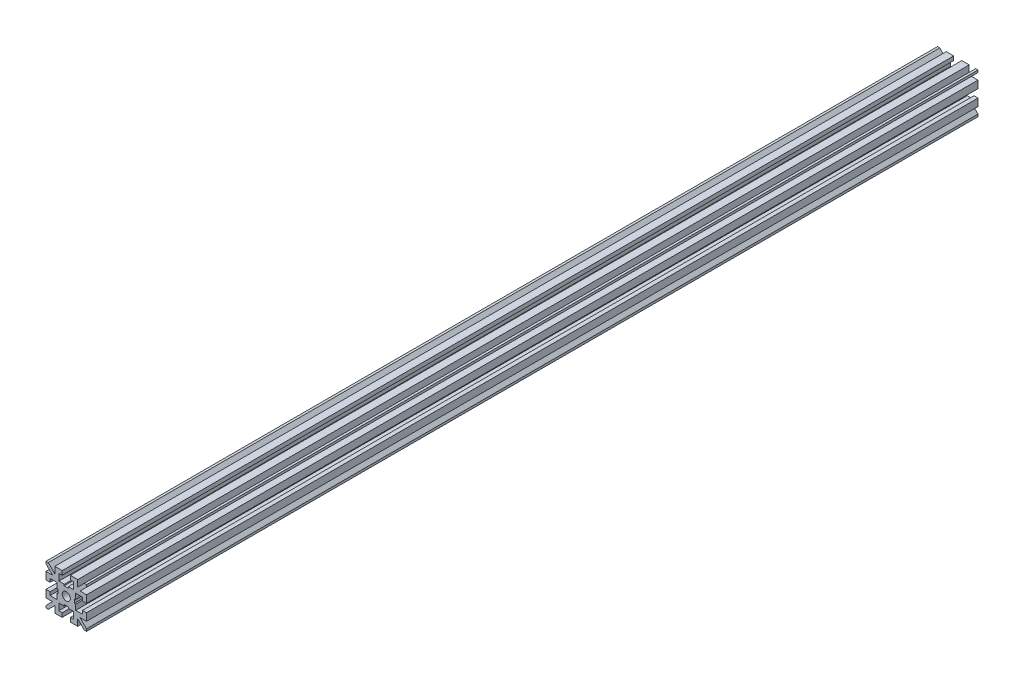
SolidWorks part; units mm, degrees
ref_plane "Front Plane" through (0, 0, 0) normal (0, 0, 1) x (1, 0, 0)
ref_plane "Top Plane" through (0, 0, 0) normal (0, 1, 0) x (1, 0, 0)
ref_plane "Right Plane" through (0, 0, 0) normal (1, 0, 0) x (0, 0, -1)
sketch "Sketch1" plane through (0, 0, 0) normal (0, 0, 1) x (1, 0, 0)
  line L1 (-9.0006, 3.7616) -> (5.9994, 3.7616)
  line L2 (-9.0006, 3.7616) -> (-9.0006, -11.2384)
  line L3 (-9.0006, -11.2384) -> (5.9994, -11.2384)
  line L4 (5.9994, 3.7616) -> (5.9994, -11.2384)
  dimension "D1" = 15
  dimension "D2" = 15
extrude "Boss-Extrude1" add sketch "Sketch1" along normal blind 330
sketch "Sketch2" plane through (0, 0, 330) normal (0, 0, 1) x (1, 0, 0)
  line L0 (-9.0006, 3.7616) -> (5.9994, -11.2384) construction
  line L1 (5.9994, 3.7616) -> (-9.0006, -11.2384) construction
  line L4 (1.9994, -4.4884) -> (1.9994, -6.4884)
  line L5 (5.9994, -3.7384) -> (1.9994, -3.7384) construction
  line L6 (5.9994, -11.2384) -> (5.9994, 3.7616) construction
  line L7 (-1.5006, 3.7616) -> (-1.5006, -3.7384) construction
  line L8 (5.9994, 3.7616) -> (-9.0006, 3.7616) construction
  line L9 (-9.0006, -3.7384) -> (-1.5006, -3.7384) construction
  line L10 (-9.0006, 3.7616) -> (-9.0006, -11.2384) construction
  line L11 (-1.5006, -11.2384) -> (-1.5006, -3.7384) construction
  line L12 (-9.0006, -11.2384) -> (5.9994, -11.2384) construction
  line L13 (1.9994, -4.4884) -> (1.4994, -4.4884)
  line L14 (1.9994, -0.9884) -> (4.4994, -0.9884)
  line L15 (1.9994, -0.9884) -> (1.9994, -2.9884)
  line L16 (1.9994, -6.4884) -> (4.4994, -6.4884)
  line L17 (4.4994, -0.9884) -> (4.4994, -6.4884)
  line L18 (-4.2506, -7.2384) -> (-4.2506, -9.7384)
  line L19 (1.9994, -2.9884) -> (1.4994, -2.9884)
  line L20 (1.4994, -4.4884) -> (1.4994, -2.9884)
  line L21 (1.4994, -3.7384) -> (-0.0006, -3.7384) construction
  line L22 (-2.2506, -7.2384) -> (-4.2506, -7.2384)
  line L23 (-2.2506, -7.2384) -> (-2.2506, -6.7384)
  line L24 (-2.2506, -6.7384) -> (-0.7506, -6.7384)
  line L25 (-0.7506, -7.2384) -> (-0.7506, -6.7384)
  line L26 (1.2494, -7.2384) -> (-0.7506, -7.2384)
  line L27 (1.2494, -7.2384) -> (1.2494, -9.7384)
  line L28 (1.2494, -9.7384) -> (-4.2506, -9.7384)
  line L29 (-5.0006, -0.9884) -> (-7.5006, -0.9884)
  line L30 (-5.0006, -2.9884) -> (-5.0006, -0.9884)
  line L31 (-5.0006, -2.9884) -> (-4.5006, -2.9884)
  line L32 (-4.5006, -2.9884) -> (-4.5006, -4.4884)
  line L33 (-5.0006, -4.4884) -> (-4.5006, -4.4884)
  line L34 (-5.0006, -6.4884) -> (-5.0006, -4.4884)
  line L35 (-5.0006, -6.4884) -> (-7.5006, -6.4884)
  line L36 (-7.5006, -6.4884) -> (-7.5006, -0.9884)
  line L37 (1.2494, -0.2384) -> (1.2494, 2.2616)
  line L38 (-0.7506, -0.2384) -> (1.2494, -0.2384)
  line L39 (-0.7506, -0.2384) -> (-0.7506, -0.7384)
  line L40 (-0.7506, -0.7384) -> (-2.2506, -0.7384)
  line L41 (-2.2506, -0.2384) -> (-2.2506, -0.7384)
  line L42 (-4.2506, -0.2384) -> (-2.2506, -0.2384)
  line L43 (-4.2506, -0.2384) -> (-4.2506, 2.2616)
  line L44 (-4.2506, 2.2616) -> (1.2494, 2.2616)
  circle A0 centre (-1.5006, -3.7384) radius 1.5
  point P60 (-1.5006, -3.7384)
  dimension "D1" = 5.5
  dimension "D2" = 2.5
  dimension "D3" = 1.5
  dimension "D4" = 2.75
  dimension "D5" = 0.5
  dimension "D6" = 1.5
  dimension "D7" = 0.75
  dimension "D8" = 4
extrude "Cut-Extrude1" cut sketch "Sketch2" against normal blind 330
sketch "Sketch3" plane through (0, 0, 330) normal (0, 0, 1) x (1, 0, 0)
  line L0 (5.9994, 3.7616) -> (-9.0006, -11.2384) construction
  line L1 (-9.0006, 3.7616) -> (5.9994, -11.2384) construction
  line L2 (5.1509, 3.7616) -> (2.7494, 1.3602)
  line L3 (5.9994, 3.7616) -> (-9.0006, 3.7616) construction
  line L4 (2.7494, 1.3602) -> (2.7494, 3.7616)
  line L5 (2.7494, 3.7616) -> (5.1509, 3.7616)
  line L6 (1.2494, -0.2384) -> (1.2494, 2.2616) construction
  line L7 (5.9994, 0.5116) -> (5.9994, 2.9131)
  line L8 (3.5979, 0.5116) -> (5.9994, 0.5116)
  line L9 (5.9994, 2.9131) -> (3.5979, 0.5116)
  line L10 (1.2494, 2.2616) -> (-4.2506, 2.2616) construction
  line L11 (-3.0006, 3.7616) -> (-0.0006, 3.7616)
  line L12 (-3.0006, 3.7616) -> (-3.0006, 2.2616)
  line L13 (-3.0006, 2.2616) -> (-0.0006, 2.2616)
  line L14 (-0.0006, 3.7616) -> (-0.0006, 2.2616)
  line L15 (-2.2506, -0.7384) -> (-0.7506, -0.7384) construction
  line L16 (2.7494, -8.8369) -> (2.7494, -11.2384)
  line L17 (2.7494, -11.2384) -> (5.1509, -11.2384)
  line L18 (5.1509, -11.2384) -> (2.7494, -8.8369)
  line L19 (5.9994, -10.3898) -> (3.5979, -7.9884)
  line L20 (3.5979, -7.9884) -> (5.9994, -7.9884)
  line L21 (5.9994, -7.9884) -> (5.9994, -10.3898)
  line L22 (5.9994, -5.2384) -> (4.4994, -5.2384)
  line L23 (5.9994, -2.2384) -> (5.9994, -5.2384)
  line L24 (5.9994, -2.2384) -> (4.4994, -2.2384)
  line L25 (4.4994, -2.2384) -> (4.4994, -5.2384)
  line L26 (-6.5991, -7.9884) -> (-9.0006, -7.9884)
  line L27 (-9.0006, -7.9884) -> (-9.0006, -10.3898)
  line L28 (-9.0006, -10.3898) -> (-6.5991, -7.9884)
  line L29 (-8.1521, -11.2384) -> (-5.7506, -8.8369)
  line L30 (-5.7506, -8.8369) -> (-5.7506, -11.2384)
  line L31 (-5.7506, -11.2384) -> (-8.1521, -11.2384)
  line L32 (-3.0006, -11.2384) -> (-3.0006, -9.7384)
  line L33 (-0.0006, -11.2384) -> (-3.0006, -11.2384)
  line L34 (-0.0006, -11.2384) -> (-0.0006, -9.7384)
  line L35 (-0.0006, -9.7384) -> (-3.0006, -9.7384)
  line L36 (-5.7506, 1.3602) -> (-5.7506, 3.7616)
  line L37 (-5.7506, 3.7616) -> (-8.1521, 3.7616)
  line L38 (-8.1521, 3.7616) -> (-5.7506, 1.3602)
  line L39 (-9.0006, 2.9131) -> (-6.5991, 0.5116)
  line L40 (-6.5991, 0.5116) -> (-9.0006, 0.5116)
  line L41 (-9.0006, 0.5116) -> (-9.0006, 2.9131)
  line L42 (-9.0006, -2.2384) -> (-7.5006, -2.2384)
  line L43 (-9.0006, -5.2384) -> (-9.0006, -2.2384)
  line L44 (-9.0006, -5.2384) -> (-7.5006, -5.2384)
  line L45 (-7.5006, -5.2384) -> (-7.5006, -2.2384)
  point P24 (-1.5006, -0.7384)
  point P27 (-1.5006, -3.7384)
  point P61 (-1.5006, -3.7384)
  dimension "D1" = 0.6
  dimension "D2" = 1.5
  dimension "D3" = 3
  dimension "D4" = 1.5
  dimension "D5" = 4
extrude "Cut-Extrude2" cut sketch "Sketch3" against normal blind 330
